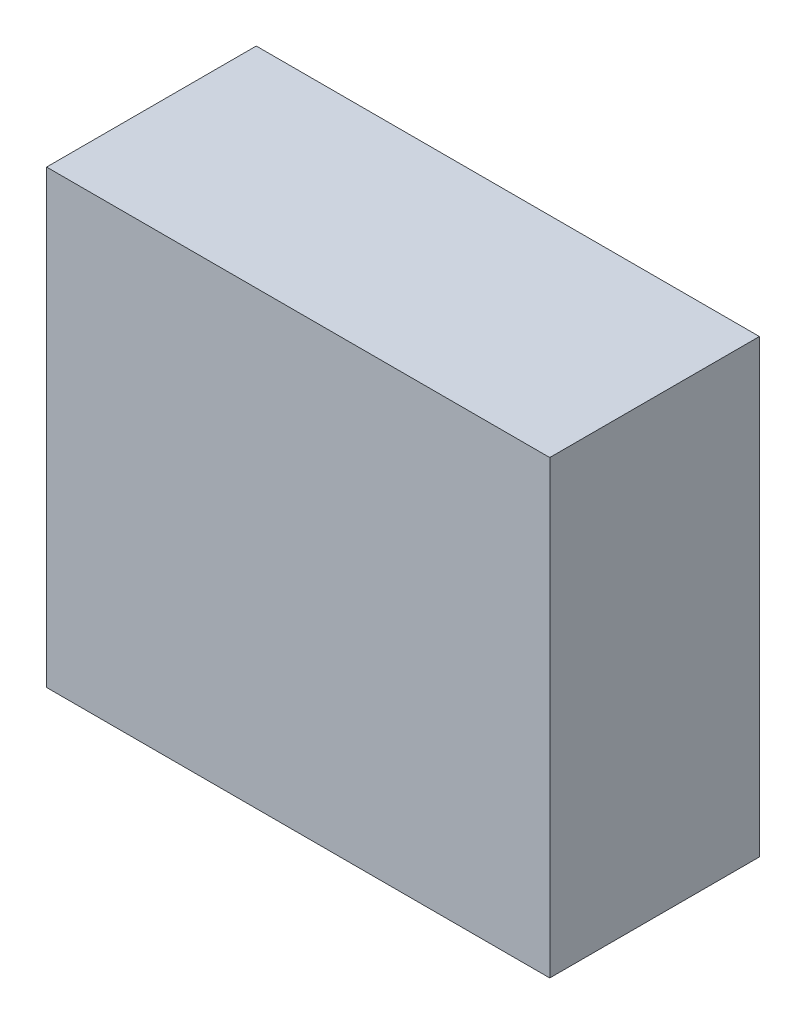
SolidWorks part; units mm, degrees
ref_plane "Front Plane" through (0, 0, 0) normal (0, 0, 1) x (1, 0, 0)
ref_plane "Top Plane" through (0, 0, 0) normal (0, 1, 0) x (1, 0, 0)
ref_plane "Right Plane" through (0, 0, 0) normal (1, 0, 0) x (0, 0, -1)
sketch "Sketch1" plane through (0, 0, 0) normal (0, 1, 0) x (1, 0, 0)
  line L1 (-240, -100) -> (240, -100)
  line L2 (-240, -100) -> (-240, 100)
  line L3 (-240, 100) -> (240, 100)
  line L4 (240, -100) -> (240, 100)
  line L5 (-240, -100) -> (240, 100) construction
  line L6 (-240, 100) -> (240, -100) construction
  point P0 (0, 0)
  dimension "D1" = 200
  dimension "D2" = 480
extrude "Boss-Extrude1" add sketch "Sketch1" along normal blind 430
